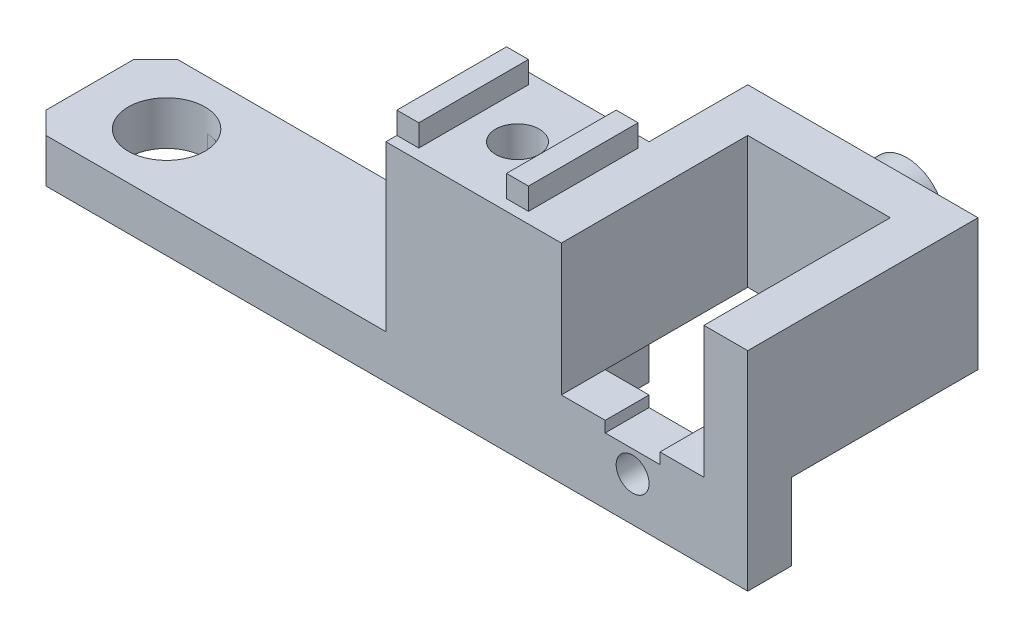
SolidWorks part; units mm, degrees
ref_plane "前视基准面" through (0, 0, 0) normal (0, 0, 1) x (1, 0, 0)
ref_plane "上视基准面" through (0, 0, 0) normal (0, 1, 0) x (1, 0, 0)
ref_plane "右视基准面" through (0, 0, 0) normal (1, 0, 0) x (0, 0, -1)
sketch "草图1" plane through (0, 0, 0) normal (0, 1, 0) x (1, 0, 0)
  line L1 (22.5, -6) -> (-22.5, -6)
  line L2 (22.5, -6) -> (22.5, 6)
  line L3 (22.5, 6) -> (-22.5, 6)
  line L4 (-22.5, -6) -> (-22.5, 6)
  line L5 (22.5, -6) -> (-22.5, 6) construction
  line L6 (22.5, 6) -> (-22.5, -6) construction
  point P0 (0, 0)
  dimension "D1" = 12
  dimension "D2" = 45
extrude "凸台-拉伸1" add sketch "草图1" along normal blind 4
sketch "草图2" plane through (0, 4, 0) normal (0, 1, 0) x (1, 0, 0)
  line L0 (22.5, 6) -> (-22.5, 6) construction
  line L1 (22.5, -6) -> (10.5, -6)
  line L2 (22.5, -6) -> (22.5, 6)
  line L3 (22.5, 6) -> (10.5, 6)
  line L4 (10.5, -6) -> (10.5, 6)
  line L5 (-22.5, 6) -> (-22.5, -6) construction
  dimension "D1" = 33
extrude "凸台-拉伸2" add sketch "草图2" along normal blind 15
sketch "草图3" plane through (0, 19, 0) normal (0, 1, 0) x (1, 0, 0)
  line L0 (10.5, 6) -> (10.5, -6) construction
  line L1 (10.5, 5) -> (12.5, 5)
  line L2 (10.5, 5) -> (10.5, -5)
  line L3 (10.5, -5) -> (12.5, -5)
  line L4 (12.5, 5) -> (12.5, -5)
  line L5 (22.5, 0) -> (0, 0) construction
  line L6 (22.5, -6) -> (22.5, 6) construction
  line L7 (16.5, 6) -> (16.5, -6) construction
  line L8 (22.5, 6) -> (10.5, 6) construction
  line L9 (10.5, -6) -> (22.5, -6) construction
  line L10 (22.5, -5) -> (20.5, -5)
  line L11 (20.5, 5) -> (20.5, -5)
  line L12 (22.5, 5) -> (20.5, 5)
  line L13 (22.5, 5) -> (22.5, -5)
  point P11 (12.5, 0)
  dimension "D1" = 2
  dimension "D2" = 10
extrude "凸台-拉伸3" add sketch "草图3" along normal blind 2
sketch "草图4" plane through (0, 0, 0) normal (0, -1, 0) x (1, 0, 0)
  line L1 (22.5, 6) -> (43.5, 6)
  line L2 (22.5, 6) -> (22.5, -15)
  line L3 (22.5, -15) -> (43.5, -15)
  line L4 (43.5, 6) -> (43.5, -15)
  dimension "D1" = 21
extrude "凸台-拉伸4" add sketch "草图4" against normal blind 19
sketch "草图5" plane through (0, 19, 0) normal (0, 1, 0) x (1, 0, 0)
  line L0 (22.5, 15) -> (43.5, -6) construction
  line L1 (22.5, 15) -> (43.5, 15) construction
  line L2 (26.5, 11) -> (39.5, 11)
  line L3 (26.5, 11) -> (26.5, -2)
  line L4 (26.5, -2) -> (39.5, -2)
  line L5 (39.5, 11) -> (39.5, -2)
  line L6 (26.5, 11) -> (39.5, -2) construction
  line L7 (26.5, -2) -> (39.5, 11) construction
  point P4 (33, 4.5)
  dimension "D1" = 4
extrude "切除-拉伸1" cut sketch "草图5" against normal through all
sketch "草图6" plane through (0, 19, 0) normal (0, 1, 0) x (1, 0, 0)
  line L0 (10.5, -6) -> (43.5, -6) construction
  line L1 (26.5, -2) -> (39.5, -2)
  line L2 (26.5, -2) -> (26.5, -6)
  line L3 (26.5, -6) -> (39.5, -6)
  line L4 (39.5, -2) -> (39.5, -6)
  line L5 (39.5, -2) -> (39.5, 11) construction
extrude "切除-拉伸2" cut sketch "草图6" against normal offset from surface (12 mm away) 7 up to face at (33, 0, -4.5)
sketch "草图7" plane through (0, 0, 6) normal (0, 0, 1) x (1, 0, 0)
  line L0 (39.5, 7) -> (26.5, 7) construction
  line L1 (30.5, 8) -> (35.5, 8)
  line L2 (30.5, 8) -> (30.5, 6)
  line L3 (30.5, 6) -> (35.5, 6)
  line L4 (35.5, 8) -> (35.5, 6)
  line L5 (30.5, 8) -> (35.5, 6) construction
  line L6 (30.5, 6) -> (35.5, 8) construction
  point P0 (33, 7)
  dimension "D1" = 1
  dimension "D2" = 5
extrude "切除-拉伸3" cut sketch "草图7" against normal up to next
sketch "草图8" plane through (0, 0, 6) normal (0, 0, 1) x (1, 0, 0)
  line L0 (-22.5, 0) -> (43.5, 0) construction
  line L1 (33, 4) -> (33, 6) construction
  line L2 (30.5, 6) -> (35.5, 6) construction
  circle A0 centre (33, 4) radius 1.5
  dimension "D1" = 4
  dimension "D2" = 3
extrude "切除-拉伸4" cut sketch "草图8" against normal up to next
chamfer "倒角1" distance 2 angle 45 2 edges at (-22.5, 2, -6) (-22.5, 2, 6)
sketch "草图9" plane through (0, 4, 0) normal (0, 1, 0) x (1, 0, 0)
  line L0 (-22.5, 4) -> (-22.5, -4) construction
  circle A0 centre (-15.5, 0) radius 3.5
  point P4 (0, 0)
  dimension "D1" = 7
  dimension "D2" = 7
extrude "切除-拉伸5" cut sketch "草图9" against normal through all both and the other way through all
sketch "草图10" plane through (0, 0, 0) normal (0, -1, 0) x (1, 0, 0)
  line L0 (-15.2812, 3.4932) -> (8.625, 1.9961)
  line L1 (8.625, -1.9961) -> (-15.2812, -3.4932)
  circle A0 centre (8.5, 0) radius 2
  circle A1 centre (-15.5, 0) radius 3.5 construction
  circle A2 centre (-15.5, 0) radius 3.5
  circle M5 centre (-15.5, 0) radius 3.5
  dimension "D1" = 4
  dimension "D2" = 24
extrude "切除-拉伸6" cut sketch "草图10" against normal blind 2 and the other way through all contours A0 L0 L1 M5 | A0
sketch "草图11" plane through (0, 19, 0) normal (0, 1, 0) x (1, 0, 0)
  line L0 (16.5, 0) -> (16.5, 6) construction
  line L1 (22.5, 6) -> (10.5, 6) construction
  circle A0 centre (16.5, 0) radius 2
  point P2 (16.5, 0.2768)
  point P6 (0, 0)
  dimension "D1" = 4
extrude "切除-拉伸7" cut sketch "草图11" against normal through all both and the other way through all
sketch "草图12" plane through (0, 0, 0) normal (0, -1, 0) x (1, 0, 0)
  circle A0 centre (16.5, 0) radius 3.5
  dimension "D1" = 7
extrude "切除-拉伸8" cut sketch "草图12" against normal blind 10 and the other way through all
sketch "草图13" plane through (0, 0, -15) normal (0, 0, -1) x (-1, 0, 0)
  line L0 (-43.5, 19) -> (-43.5, 0) construction
  line L1 (-22.5, 0) -> (-43.5, 0)
  line L2 (-22.5, 0) -> (-22.5, 7)
  line L3 (-22.5, 7) -> (-43.5, 7)
  line L4 (-43.5, 0) -> (-43.5, 7)
  dimension "D1" = 7
extrude "切除-拉伸9" cut sketch "草图13" against normal up to surface (17 mm away) up to face at (34.5, 4, 2)
sketch "草图14" plane through (0, 0, -15) normal (0, 0, -1) x (-1, 0, 0)
  line L0 (-43.5, 19) -> (-22.5, 7) construction
  circle A0 centre (-33, 13) radius 3.5
  dimension "D1" = 7
extrude "凸台-拉伸5" add sketch "草图14" along normal blind 4
